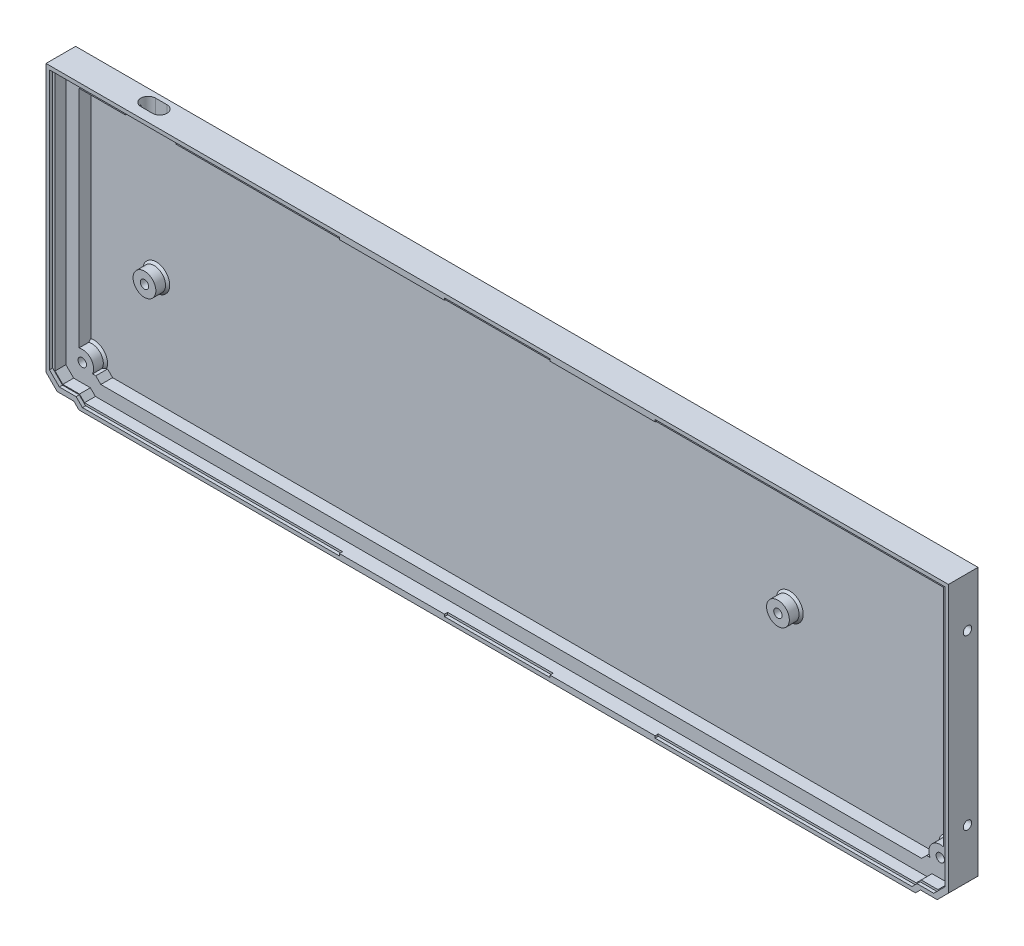
SolidWorks part; units mm, degrees
ref_plane "Přední rovina" through (0, 0, 0) normal (0, 0, 1) x (1, 0, 0)
ref_plane "Horní rovina" through (0, 0, 0) normal (0, 1, 0) x (1, 0, 0)
ref_plane "Pravá rovina" through (0, 0, 0) normal (1, 0, 0) x (0, 0, -1)
sketch "Skica3" plane through (0, 0, 0) normal (0, 0, 1) x (1, 0, 0)
  line L0 (0, 0) -> (415.1053, 0) construction
  line L1 (415.1053, 0) -> (416.6927, -1.5875) construction
  line L2 (416.6927, -1.5875) -> (416.6927, -119.8485) construction
  line L3 (0, 0) -> (-1.5875, -1.5875) construction
  line L4 (-1.5875, -1.5875) -> (-1.5875, -119.8485) construction
  line L5 (-1.5875, -119.8485) -> (0.7934, -122.2292) construction
  line L6 (0.7934, -122.2292) -> (8.7304, -122.2292) construction
  line L7 (8.7304, -122.2292) -> (11.1113, -124.61) construction
  line L8 (11.1113, -124.61) -> (403.9933, -124.61) construction
  line L9 (403.9933, -124.61) -> (406.3744, -122.2294) construction
  line L10 (406.3744, -122.2294) -> (414.3114, -122.2294) construction
  line L11 (416.6927, -119.8485) -> (414.3114, -122.2294) construction
  line L12 (2.4125, -4) -> (412.6927, -4)
  line L13 (412.6927, -4) -> (412.6927, -4)
  line L14 (412.6927, -4) -> (412.6927, -118.1914)
  line L15 (412.6927, -118.1914) -> (412.6547, -118.2294)
  line L16 (404.7177, -118.2294) -> (412.6547, -118.2294)
  line L17 (402.3367, -120.61) -> (404.7177, -118.2294)
  line L18 (12.7681, -120.61) -> (402.3367, -120.61)
  line L19 (10.3872, -118.2292) -> (12.7681, -120.61)
  line L20 (2.4502, -118.2292) -> (10.3872, -118.2292)
  line L21 (2.4125, -118.1915) -> (2.4502, -118.2292)
  line L22 (2.4125, -4) -> (2.4125, -118.1915)
  line L23 (2.4125, -4) -> (2.4125, -4)
  line L24 (-1.5875, -119.8485) -> (415.1053, 0) construction
  line L26 (0, 0) -> (416.6927, -119.8485) construction
  dimension "D1" = 135
  dimension "D2" = 135
  dimension "D3" = 4
  dimension "D4" = 2.245
  dimension "D5" = 2.245
  dimension "D6" = 118.261
  dimension "D7" = 118.261
  dimension "D8" = 3.367
  dimension "D9" = 7.937
  dimension "D10" = 3.367
  dimension "D11" = 392.882
  dimension "D12" = 3.367
  dimension "D13" = 7.937
  dimension "D14" = 3.3674
extrude "Přidat vysunutím1" add sketch "Skica3" along normal blind 5.6
shell "Skořepina1" thickness 1.8
sketch "Skica7" plane through (0, 0, 5.6) normal (0, 0, 1) x (1, 0, 0)
  line L20 (-6.5875, 5) -> (-6.5875, -121.9196)
  line L21 (-6.5875, -121.9196) -> (-1.2775, -127.2292)
  line L22 (-1.2775, -127.2292) -> (6.6595, -127.2292)
  line L23 (6.6595, -127.2292) -> (9.0403, -129.61)
  line L24 (9.0403, -129.61) -> (406.0641, -129.61)
  line L25 (406.0641, -129.61) -> (408.4452, -127.2294)
  line L26 (408.4452, -127.2294) -> (416.3822, -127.2294)
  line L27 (416.3822, -127.2294) -> (421.6927, -121.9198)
  line L28 (421.6927, -121.9198) -> (421.6927, 5)
  line L29 (421.6927, 5) -> (-6.5875, 5)
  line L30 (-6.5875, 5) -> (-6.5875, -121.9196)
  line L31 (-6.5875, -121.9196) -> (-1.2775, -127.2292)
  line L32 (-1.2775, -127.2292) -> (6.6595, -127.2292)
  line L33 (6.6595, -127.2292) -> (9.0403, -129.61)
  line L34 (9.0403, -129.61) -> (406.0641, -129.61)
  line L35 (406.0641, -129.61) -> (408.4452, -127.2294)
  line L36 (408.4452, -127.2294) -> (416.3822, -127.2294)
  line L37 (416.3822, -127.2294) -> (421.6927, -121.9198)
  line L38 (421.6927, -121.9198) -> (421.6927, 5)
  line L39 (421.6927, 5) -> (-6.5875, 5)
  line L40 (-3.7875, 2.2) -> (-3.7875, -120.7598)
  line L41 (-3.7875, -120.7598) -> (-0.1178, -124.4292)
  line L42 (-0.1178, -124.4292) -> (7.8192, -124.4292)
  line L43 (7.8192, -124.4292) -> (10.2001, -126.81)
  line L44 (10.2001, -126.81) -> (404.9045, -126.81)
  line L45 (404.9045, -126.81) -> (407.2855, -124.4294)
  line L46 (407.2855, -124.4294) -> (415.2225, -124.4294)
  line L47 (415.2225, -124.4294) -> (418.8927, -120.7598)
  line L48 (418.8927, -120.7598) -> (418.8927, 2.2)
  line L49 (418.8927, 2.2) -> (-3.7875, 2.2)
  line L50 (-3.7875, 2.2) -> (-3.7875, -120.7598)
  line L51 (-3.7875, -120.7598) -> (-0.1178, -124.4292)
  line L52 (-0.1178, -124.4292) -> (7.8192, -124.4292)
  line L53 (7.8192, -124.4292) -> (10.2001, -126.81)
  line L54 (10.2001, -126.81) -> (404.9045, -126.81)
  line L55 (404.9045, -126.81) -> (407.2855, -124.4294)
  line L56 (407.2855, -124.4294) -> (415.2225, -124.4294)
  line L57 (415.2225, -124.4294) -> (418.8927, -120.7598)
  line L58 (418.8927, -120.7598) -> (418.8927, 2.2)
  line L59 (418.8927, 2.2) -> (-3.7875, 2.2)
  dimension "D2" = 4.4
  dimension "D1" = 7.2
extrude "Přidat vysunutím3" add sketch "Skica7" along normal blind 5.15 separate body
sketch "Skica8" plane through (0, 0, 5.6) normal (0, 0, -1) x (-1, 0, 0)
  line L0 (-421.6927, 5) -> (6.5875, 5)
  line L1 (6.5875, 5) -> (6.5875, -121.9196)
  line L2 (6.5875, 5) -> (6.5875, -121.9196) construction
  line L3 (6.5875, -121.9196) -> (1.2775, -127.2292)
  line L4 (1.2775, -127.2292) -> (-6.6595, -127.2292)
  line L5 (-6.6595, -127.2292) -> (-9.0403, -129.61)
  line L6 (-9.0403, -129.61) -> (-406.0641, -129.61)
  line L7 (-406.0641, -129.61) -> (-408.4452, -127.2294)
  line L8 (-408.4452, -127.2294) -> (-416.3822, -127.2294)
  line L9 (-416.3822, -127.2294) -> (-421.6927, -121.9198)
  line L10 (-421.6927, -121.9198) -> (-421.6927, 5)
  line L11 (-0.6125, -2.2) -> (-0.6125, -118.9371)
  line L12 (-414.4927, -2.2) -> (-0.6125, -2.2) construction
  line L13 (-0.6125, -2.2) -> (-0.6125, -118.9371) construction
  line L14 (-0.6125, -118.9371) -> (-1.7047, -120.0292)
  line L15 (-1.7047, -120.0292) -> (-9.6417, -120.0292)
  line L16 (-9.6417, -120.0292) -> (-12.0226, -122.41)
  line L17 (-12.0226, -122.41) -> (-403.0822, -122.41)
  line L18 (-403.0822, -122.41) -> (-405.4632, -120.0294)
  line L19 (-405.4632, -120.0294) -> (-413.4002, -120.0294) construction
  line L20 (-405.4632, -120.0294) -> (-413.4002, -120.0294)
  line L21 (-413.4002, -120.0294) -> (-414.4927, -118.9371) construction
  line L22 (-413.4002, -120.0294) -> (-414.4927, -118.9371)
  line L23 (-414.4927, -118.9371) -> (-414.4927, -2.2)
  line L24 (-414.4927, -2.2) -> (-0.6125, -2.2)
extrude "Přidat vysunutím4" add sketch "Skica8" along normal up to surface (7.4 mm away) up to face at (207.5525, -96.7211, -1.8)
sketch "Skica11" plane through (0, 0, 10.75) normal (0, 0, 1) x (1, 0, 0)
  line L0 (207.5526, 3.195) -> (207.5526, 5) construction
  line L1 (421.6927, 5) -> (-6.5875, 5) construction
  line L2 (207.5522, -127.805) -> (207.5522, -129.61) construction
  line L3 (9.0403, -129.61) -> (406.0641, -129.61) construction
  line L4 (-4.9474, -58.4598) -> (-6.5875, -58.4598) construction
  line L5 (-6.5875, 5) -> (-6.5875, -121.9196) construction
  line L6 (420.0526, -58.4599) -> (421.6927, -58.4599) construction
  line L7 (421.6927, -121.9198) -> (421.6927, 5) construction
  line L8 (404.9045, -126.81) -> (407.2855, -124.4294) construction
  line L9 (415.2225, -124.4294) -> (418.8927, -120.7598) construction
  line L10 (7.8192, -124.4292) -> (10.2001, -126.81) construction
  line L11 (-3.7875, -120.7598) -> (-0.1178, -124.4292) construction
  line L13 (407.2855, -124.4294) -> (415.2225, -124.4294) construction
  line L14 (-0.1178, -124.4292) -> (7.8192, -124.4292) construction
  line L30 (420.0526, 3.195) -> (-4.9474, 3.195)
  line L31 (-4.9474, 3.195) -> (-4.9474, -120.1146)
  line L32 (-4.9474, -120.1146) -> (-0.24, -124.8217)
  line L33 (-0.24, -124.8217) -> (7.697, -124.8217)
  line L34 (7.697, -124.8217) -> (10.6804, -127.805)
  line L35 (10.6804, -127.805) -> (404.4241, -127.805)
  line L36 (404.4241, -127.805) -> (406.8051, -125.4244)
  line L37 (406.8051, -125.4244) -> (414.7421, -125.4244)
  line L38 (414.7421, -125.4244) -> (420.0526, -120.1148)
  line L39 (420.0526, -120.1148) -> (420.0526, 3.195)
  line L45 (421.6927, 5) -> (-6.5875, 5)
  line L46 (-6.5875, 5) -> (-6.5875, -121.9196)
  line L47 (-6.5875, -121.9196) -> (-1.2775, -127.2292)
  line L48 (-1.2775, -127.2292) -> (6.6595, -127.2292)
  line L49 (6.6595, -127.2292) -> (9.0403, -129.61)
  line L50 (9.0403, -129.61) -> (406.0641, -129.61)
  line L51 (406.0641, -129.61) -> (408.4452, -127.2294)
  line L52 (408.4452, -127.2294) -> (416.3822, -127.2294)
  line L53 (416.3822, -127.2294) -> (421.6927, -121.9198)
  line L54 (421.6927, -121.9198) -> (421.6927, 5)
  line L55 (421.6927, 5) -> (-6.5875, 5)
  line L56 (-6.5875, 5) -> (-6.5875, -121.9196)
  line L57 (-6.5875, -121.9196) -> (-1.2775, -127.2292)
  line L58 (-1.2775, -127.2292) -> (6.6595, -127.2292)
  line L59 (6.6595, -127.2292) -> (9.0403, -129.61)
  line L60 (9.0403, -129.61) -> (406.0641, -129.61)
  line L61 (406.0641, -129.61) -> (408.4452, -127.2294)
  line L62 (408.4452, -127.2294) -> (416.3822, -127.2294)
  line L63 (416.3822, -127.2294) -> (421.6927, -121.9198)
  line L64 (421.6927, -121.9198) -> (421.6927, 5)
  point P0 (207.5523, -63.11)
  point P2 (207.5523, -63.11)
  dimension "D1" = 131
  dimension "D2" = 425
  dimension "D3" = 0
extrude "Přidat vysunutím5" add sketch "Skica11" along normal blind 1.5
sketch "Skica14" plane through (0, 0, 10.75) normal (0, 0, 1) x (1, 0, 0)
  line L0 (418.8927, 2.2) -> (-3.7875, 2.2) construction
  line L1 (182.5326, 2.2) -> (132.6326, 2.2)
  line L2 (182.5326, 2.2) -> (182.5326, 3.195)
  line L3 (182.5326, 3.195) -> (132.6326, 3.195)
  line L4 (132.6326, 2.2) -> (132.6326, 3.195)
  line L5 (420.0526, 3.195) -> (-4.9474, 3.195) construction
  line L6 (418.8927, 2.2) -> (-3.7875, 2.2) construction
  line L7 (232.5726, 2.2) -> (282.4726, 2.2)
  line L8 (232.5726, 2.2) -> (232.5726, 3.195)
  line L9 (232.5726, 3.195) -> (282.4726, 3.195)
  line L10 (282.4726, 2.2) -> (282.4726, 3.195)
  line L11 (207.5526, 3.195) -> (207.5522, -127.805) construction
  line L12 (10.6804, -127.805) -> (404.4241, -127.805) construction
  line L13 (10.2001, -126.81) -> (404.9045, -126.81) construction
  line L14 (232.5722, -126.81) -> (282.4722, -126.81)
  line L15 (232.5722, -126.81) -> (232.5722, -127.805)
  line L16 (232.5722, -127.805) -> (282.4722, -127.805)
  line L17 (282.4722, -126.81) -> (282.4722, -127.805)
  line L18 (10.6804, -127.805) -> (404.4241, -127.805) construction
  line L20 (182.5322, -126.81) -> (132.6322, -126.81)
  line L21 (182.5322, -126.81) -> (182.5322, -127.805)
  line L22 (182.5322, -127.805) -> (132.6322, -127.805)
  line L23 (132.6322, -126.81) -> (132.6322, -127.805)
  dimension "D1" = 49.9
  dimension "D2" = 49.9
  dimension "D3" = 25.02
  dimension "D4" = 25.02
  dimension "D5" = 49.9
  dimension "D6" = 49.9
  dimension "D7" = 25.02
  dimension "D8" = 25.02
extrude "Přidat vysunutím6" add sketch "Skica14" along normal up to surface (1.5 mm away) up to face at (207.5524, -100.1977, 12.25)
sketch "Skica15" plane through (0, 0, 0) normal (0, 0, 1) x (1, 0, 0)
  line L1 (34.9015, 4.5) -> (37.9015, 4.5)
  line L2 (34.9015, 4.5) -> (34.9015, -4.5)
  line L3 (34.9015, -4.5) -> (37.9015, -4.5)
  line L4 (37.9015, 4.5) -> (37.9015, -4.5)
  line L5 (34.9015, 4.5) -> (37.9015, -4.5) construction
  line L6 (34.9015, -4.5) -> (37.9015, 4.5) construction
  line L20 (-1.5875, 0) -> (-1.5875, -119.8485)
  line L21 (-1.5875, -119.8485) -> (0.7934, -122.2292)
  line L22 (0.7934, -122.2292) -> (8.7304, -122.2292)
  line L23 (8.7304, -122.2292) -> (11.1113, -124.61)
  line L24 (11.1113, -124.61) -> (403.9933, -124.61)
  line L25 (403.9933, -124.61) -> (406.3744, -122.2294)
  line L26 (406.3744, -122.2294) -> (414.3114, -122.2294)
  line L27 (414.3114, -122.2294) -> (416.6927, -119.8485)
  line L28 (416.6927, -119.8485) -> (416.6927, 0)
  line L29 (416.6927, 0) -> (-1.5875, 0)
  line L30 (-1.5875, 0) -> (-1.5875, -119.8485) construction
  line L31 (-1.5875, -119.8485) -> (0.7934, -122.2292) construction
  line L32 (0.7934, -122.2292) -> (8.7304, -122.2292) construction
  line L33 (8.7304, -122.2292) -> (11.1113, -124.61) construction
  line L34 (11.1113, -124.61) -> (403.9933, -124.61) construction
  line L35 (403.9933, -124.61) -> (406.3744, -122.2294) construction
  line L36 (406.3744, -122.2294) -> (414.3114, -122.2294) construction
  line L37 (414.3114, -122.2294) -> (416.6927, -119.8485) construction
  line L38 (416.6927, -119.8485) -> (416.6927, 0) construction
  line L39 (416.6927, 0) -> (-1.5875, 0) construction
  circle A0 centre (3.9685, -115.9542) radius 5.4
  circle A1 centre (33.4915, -69.051) radius 5.4
  circle A2 centre (411.1977, -115.8794) radius 5.4
  circle A3 centre (334.1477, -53.972) radius 5.4
  point P2 (-1.4315, -115.9542)
  point P3 (3.9685, -121.3542)
  point P4 (28.0915, -69.051)
  point P8 (33.4915, -74.451)
  point P12 (411.1977, -121.2794)
  point P13 (416.5977, -115.8794)
  point P17 (334.1477, -48.572)
  point P19 (339.5477, -53.972)
  point P21 (36.4015, 0)
  point P23 (36.4015, 0)
  dimension "D2" = 0.156
  dimension "D4" = 10.8
  dimension "D7" = 10.8
  dimension "D10" = 10.8
  dimension "D13" = 10.8
  dimension "D3" = 0.875
  dimension "D5" = 29.679
  dimension "D6" = 50.159
  dimension "D8" = 0.095
  dimension "D9" = 0.95
  dimension "D11" = 77.145
  dimension "D12" = 48.572
  dimension "D14" = 37.989
  dimension "D15" = 9
  dimension "D16" = 3
  dimension "D1" = 4
extrude "Přidat vysunutím7" add sketch "Skica15" along normal blind 5.6
sketch "Skica16" plane through (0, 0, 5.6) normal (0, 0, 1) x (1, 0, 0)
  circle A0 centre (3.9685, -115.9542) radius 2
  circle A1 centre (33.4915, -69.051) radius 2
  circle A2 centre (334.1477, -53.972) radius 2
  circle A3 centre (411.1977, -115.8794) radius 2
  dimension "D1" = 4
  dimension "D2" = 4
  dimension "D3" = 4
  dimension "D4" = 4
extrude "Odebrat vysunutím1" cut sketch "Skica16" against normal blind 5.75
chamfer "Zkosení1" distance 1 angle 45 4 edges at (407.0694, -112.3984, 0) (8.0492, -112.4175, 0) (38.8915, -69.051, 0) (339.5477, -53.972, 0)
sketch "Skica17" plane through (0, 0, 5.6) normal (0, 0, 1) x (1, 0, 0)
  line L0 (34.9015, -4.5) -> (37.9015, -4.5) construction
  line L1 (24.4015, -11.2) -> (48.4015, -11.2)
  line L2 (24.4015, -11.2) -> (24.4015, 2.2)
  line L3 (24.4015, 2.2) -> (48.4015, 2.2)
  line L4 (48.4015, -11.2) -> (48.4015, 2.2)
  line L5 (24.4015, -11.2) -> (48.4015, 2.2) construction
  line L6 (24.4015, 2.2) -> (48.4015, -11.2) construction
  line L7 (418.8927, 2.2) -> (-3.7875, 2.2) construction
  point P0 (36.4015, -4.5)
  dimension "D1" = 24
extrude "Odebrat vysunutím2" cut sketch "Skica17" against normal blind 1.6
sketch "Skica18" plane through (0, -4.5, 0) normal (0, -1, 0) x (1, 0, 0)
  line L0 (33.6515, 4) -> (39.1515, 4) construction
  line L1 (37.9015, 4) -> (34.9015, 4) construction
  line L2 (37.9015, 4) -> (48.4015, 4) construction
  line L3 (33.6515, 7.5) -> (39.1515, 7.5)
  line L4 (33.6515, 0.5) -> (39.1515, 0.5)
  arc A0 (33.6515, 7.5) -> (33.6515, 0.5) centre (33.6515, 4) ccw
  arc A1 (39.1515, 0.5) -> (39.1515, 7.5) centre (39.1515, 4) ccw
  point P6 (36.4015, 4)
  point P11 (30.1515, 4)
  point P12 (42.6515, 4)
  dimension "D1" = 12.5
  dimension "D2" = 7
extrude "Odebrat vysunutím3" cut sketch "Skica18" against normal up to surface (9.5 mm away) up to face at (207.5526, 5, 5.225)
sketch "Skica23" plane through (-6.5875, 0, 0) normal (-1, 0, 0) x (0, 0, 1)
  line L2 (-1.8, 5) -> (-1.8, -121.9196) construction
  line L4 (-1.8, -58.4598) -> (12.25, -58.4598) construction
  line L5 (12.25, 5) -> (12.25, -121.9196) construction
  circle A0 centre (3.2, -18.4598) radius 2
  circle A1 centre (3.2, -98.4598) radius 2
  point P8 (-1.8, -58.4598)
  dimension "D2" = 4
  dimension "D3" = 4
  dimension "D1" = 40
  dimension "D4" = 5
extrude "Odebrat vysunutím4" cut sketch "Skica23" against normal blind 5.7
sketch "Skica24" plane through (421.6927, 0, 0) normal (1, 0, 0) x (0, 0, -1)
  line L0 (1.8, -58.4599) -> (-12.25, -58.4599) construction
  line L1 (1.8, -121.9198) -> (1.8, 5) construction
  line L2 (-12.25, -121.9198) -> (-12.25, 5) construction
  circle A0 centre (-3.2, -18.4599) radius 2
  circle A1 centre (-3.2, -98.4599) radius 2
  dimension "D1" = 4
  dimension "D2" = 4
  dimension "D3" = 40
  dimension "D4" = 5
extrude "Odebrat vysunutím5" cut sketch "Skica24" against normal blind 5.7
sketch "Skica25" plane through (0, 0, -1.8) normal (0, 0, -1) x (-1, 0, 0)
  line L0 (-421.6927, -121.9198) -> (-421.6927, 5) construction
  line L1 (-421.6927, 5) -> (6.5875, 5) construction
  line L2 (6.5875, 5) -> (6.5875, -121.9196) construction
  line L3 (-9.0403, -129.61) -> (-406.0641, -129.61) construction
  circle A0 centre (-401.6927, -15) radius 6.25
  circle A1 centre (-13.4125, -15) radius 6.25
  circle A2 centre (-388.4452, -109.61) radius 6.25
  circle A3 centre (-26.6595, -109.61) radius 6.25
  dimension "D1" = 12.5
  dimension "D2" = 12.5
  dimension "D3" = 12.5
  dimension "D4" = 12.5
  dimension "D5" = 20
  dimension "D6" = 20
  dimension "D7" = 20
  dimension "D8" = 20
  dimension "D9" = 20
  dimension "D10" = 20
  dimension "D11" = 20
  dimension "D12" = 20
extrude "Odebrat vysunutím6" cut sketch "Skica25" against normal blind 1.5
